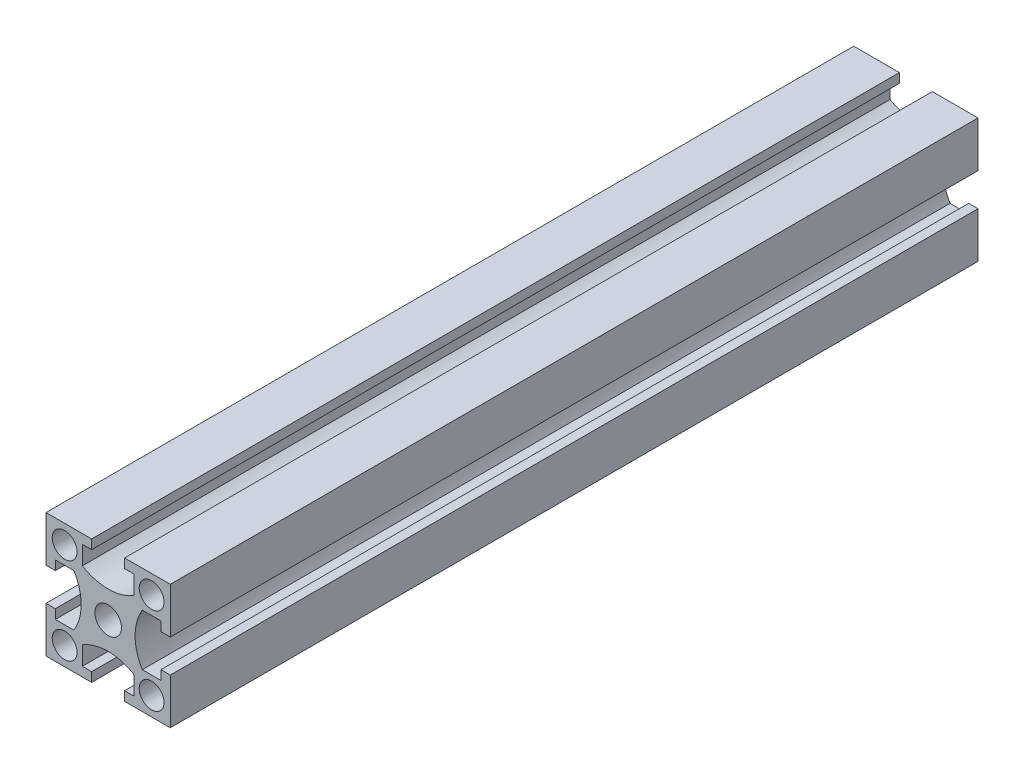
SolidWorks part; units mm, degrees
material "6061-T6 (SS)"
ref_plane "정면" through (0, 0, 0) normal (0, 0, 1) x (1, 0, 0)
ref_plane "윗면" through (0, 0, 0) normal (0, 1, 0) x (1, 0, 0)
ref_plane "우측면" through (0, 0, 0) normal (1, 0, 0) x (0, 0, -1)
sketch "스케치1" plane through (0, 0, 0) normal (0, 0, 1) x (1, 0, 0)
  line L1 (-10, 10) -> (10, 10)
  line L2 (-10, 10) -> (-10, -10)
  line L3 (-10, -10) -> (10, -10)
  line L4 (10, 10) -> (10, -10)
  line L5 (-10, 10) -> (10, -10) construction
  line L6 (-10, -10) -> (10, 10) construction
  point P0 (0, 0)
  dimension "D1" = 20
  dimension "D2" = 20
extrude "보스-돌출1" add sketch "스케치1" along normal blind 130
sketch "스케치2" plane through (0, 0, 130) normal (0, 0, 1) x (1, 0, 0)
  line L0 (-2.65, 10) -> (-2.65, 8.5)
  line L1 (10, 10) -> (-10, 10) construction
  line L2 (-2.65, 8.5) -> (-4.15, 8.5)
  line L3 (-4.15, 8.5) -> (-4.15, 5.5)
  line L4 (-2.65, 10) -> (2.65, 10)
  line L5 (2.65, 10) -> (2.65, 8.5)
  line L6 (2.65, 8.5) -> (4.15, 8.5)
  line L7 (4.15, 8.5) -> (4.15, 5.5)
  line L8 (10, 2.65) -> (8.5, 2.65)
  line L9 (8.5, 2.65) -> (8.5, 4.15)
  line L10 (8.5, 4.15) -> (5.5, 4.15)
  line L11 (10, 2.65) -> (10, -2.65)
  line L12 (10, -2.65) -> (8.5, -2.65)
  line L13 (8.5, -2.65) -> (8.5, -4.15)
  line L14 (8.5, -4.15) -> (5.5, -4.15)
  line L15 (2.65, -10) -> (2.65, -8.5)
  line L16 (2.65, -8.5) -> (4.15, -8.5)
  line L17 (4.15, -8.5) -> (4.15, -5.5)
  line L18 (2.65, -10) -> (-2.65, -10)
  line L19 (-2.65, -10) -> (-2.65, -8.5)
  line L20 (-2.65, -8.5) -> (-4.15, -8.5)
  line L21 (-4.15, -8.5) -> (-4.15, -5.5)
  line L22 (-10, -2.65) -> (-8.5, -2.65)
  line L23 (-8.5, -2.65) -> (-8.5, -4.15)
  line L24 (-8.5, -4.15) -> (-5.5, -4.15)
  line L25 (-10, -2.65) -> (-10, 2.65)
  line L26 (-10, 2.65) -> (-8.5, 2.65)
  line L27 (-8.5, 2.65) -> (-8.5, 4.15)
  line L28 (-8.5, 4.15) -> (-5.5, 4.15)
  arc A1 (-4.15, 5.5) -> (4.15, 5.5) centre (0, 12.3394) ccw
  arc A2 (5.5, 4.15) -> (5.5, -4.15) centre (12.3394, 0) ccw
  arc A3 (4.15, -5.5) -> (-4.15, -5.5) centre (0, -12.3394) ccw
  arc A4 (-5.5, -4.15) -> (-5.5, 4.15) centre (-12.3394, 0) ccw
  circle A5 centre (0, 0) radius 2.15
  circle A6 centre (-7, 7) radius 2
  circle A7 centre (7, 7) radius 2
  circle A8 centre (7, -7) radius 2
  circle A9 centre (-7, -7) radius 2
  point P4 (-2.65, 9.25)
  point P43 (0, 0)
  dimension "D2" = 1.5
  dimension "D8" = 4.3
  dimension "D9" = 4
  dimension "D10" = 4
  dimension "D11" = 4
  dimension "D12" = 4
  dimension "D21" = 8
  dimension "D1" = 5.3
  dimension "D3" = 8.3
  dimension "D4" = 4.15
  dimension "D5" = 2.65
  dimension "D6" = 4
  dimension "D7" = 3
  dimension "D13" = 14
  dimension "D14" = 7
  dimension "D15" = 7
  dimension "D16" = 7
  dimension "D17" = 14
  dimension "D18" = 7
  dimension "D19" = 7
  dimension "D20" = 7
extrude "컷-돌출1" cut sketch "스케치2" against normal blind 300
